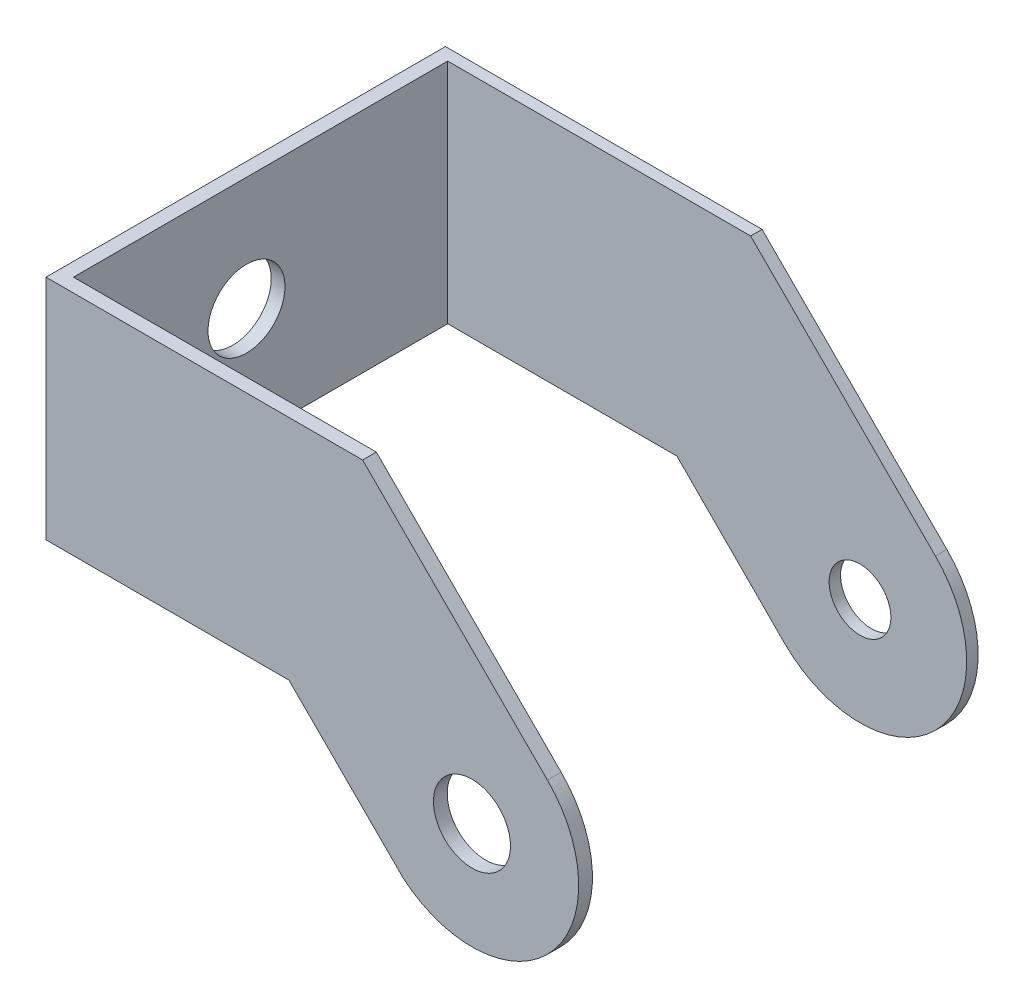
SolidWorks part; units mm, degrees
ref_plane "Plano frontal" through (0, 0, 0) normal (0, 0, 1) x (1, 0, 0)
ref_plane "Plano superior" through (0, 0, 0) normal (0, 1, 0) x (1, 0, 0)
ref_plane "Plano direito" through (0, 0, 0) normal (1, 0, 0) x (0, 0, -1)
sketch "Esboço1" plane through (0, 0, 0) normal (0, 0, 1) x (1, 0, 0)
  line L0 (9.8995, 9.8995) -> (-14.3456, 34.1445)
  line L2 (-8.9718, -10.7474) -> (-24.0208, 4.3015)
  line L4 (-24.0208, 4.3015) -> (-55.8823, 4.3015)
  line L5 (-55.8823, 4.3015) -> (-55.8823, 34.1445)
  line L6 (-55.8823, 34.1445) -> (-14.3456, 34.1445)
  arc A0 (-8.9718, -10.7474) -> (9.8995, 9.8995) centre (0, 0) ccw
  circle A1 centre (0, 0) radius 5.05
extrude "Ressalto-extrusão2" add sketch "Esboço1" along normal blind 1.8
ref_plane "Plano1" through (-55.8823, 0, 0) normal (1, 0, 0) x (0, 0, -1)
sketch "Esboço2" plane through (-55.8823, 0, 0) normal (1, 0, 0) x (0, 0, -1)
  line L0 (0, 34.1445) -> (0, 4.3015)
  line L1 (0, 34.1445) -> (49.1, 34.1445)
  line L2 (0, 4.3015) -> (49.1, 4.3015)
  line L3 (49.1, 34.1445) -> (49.1, 4.3015)
  circle A0 centre (22.7, 19.2135) radius 5.05
extrude "Ressalto-extrusão3" add sketch "Esboço2" along normal blind 1.8
ref_plane "Plano2" through (0, 0, -49.1) normal (0, 0, -1) x (-1, 0, 0)
sketch "Esboço3" plane through (0, 0, -49.1) normal (0, 0, -1) x (-1, 0, 0)
  line L0 (-9.8995, 9.8995) -> (14.3456, 34.1445)
  line L1 (9.8995, -9.8995) -> (24.0208, 4.3015)
  line L2 (24.0208, 4.3015) -> (55.8823, 4.3015)
  line L3 (55.8823, 4.3015) -> (55.8823, 34.1445)
  line L4 (55.8823, 34.1445) -> (14.3456, 34.1445)
  arc A0 (-9.8995, 9.8995) -> (9.8995, -9.8995) centre (0, 0) ccw
  circle A1 centre (0, 0) radius 4.05
extrude "Ressalto-extrusão5" add sketch "Esboço3" along normal blind 1.5
